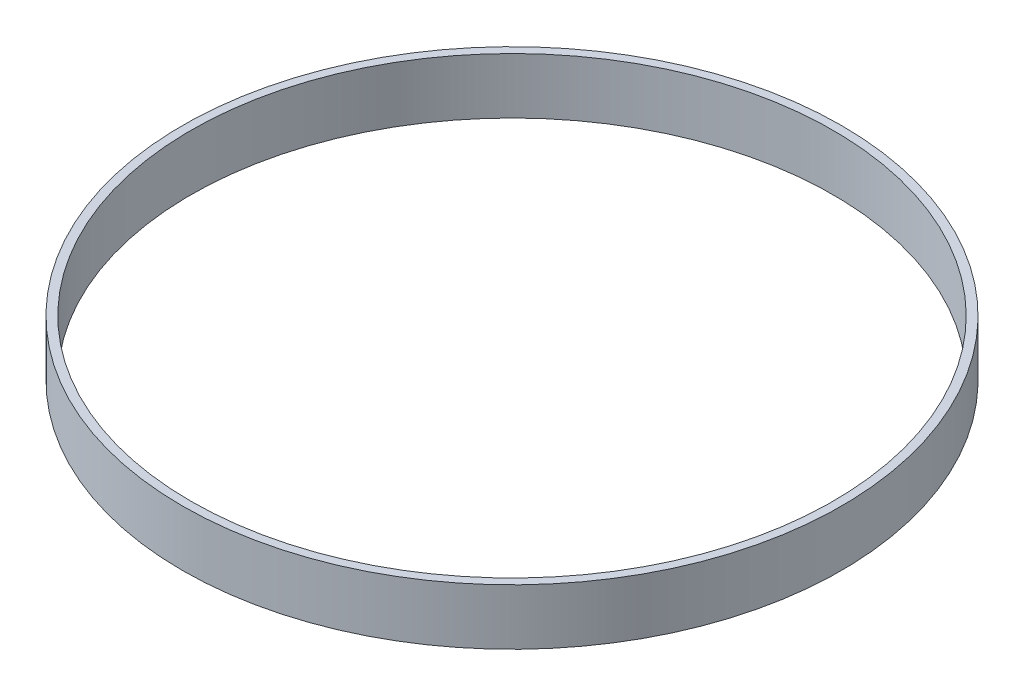
SolidWorks part; units mm, degrees
ref_plane "Front Plane" through (0, 0, 0) normal (0, 0, 1) x (1, 0, 0)
ref_plane "Top Plane" through (0, 0, 0) normal (0, 1, 0) x (1, 0, 0)
ref_plane "Right Plane" through (0, 0, 0) normal (1, 0, 0) x (0, 0, -1)
other "Configuration Table"
sketch "草图1" plane through (0, 0, 0) normal (0, 1, 0) x (1, 0, 0)
  circle A0 centre (0, 0) radius 57.5
  circle A1 centre (0, 0) radius 59
  dimension "D1" = 115
  dimension "D2" = 118
extrude "凸台-拉伸1" add sketch "草图1" along normal blind 10
